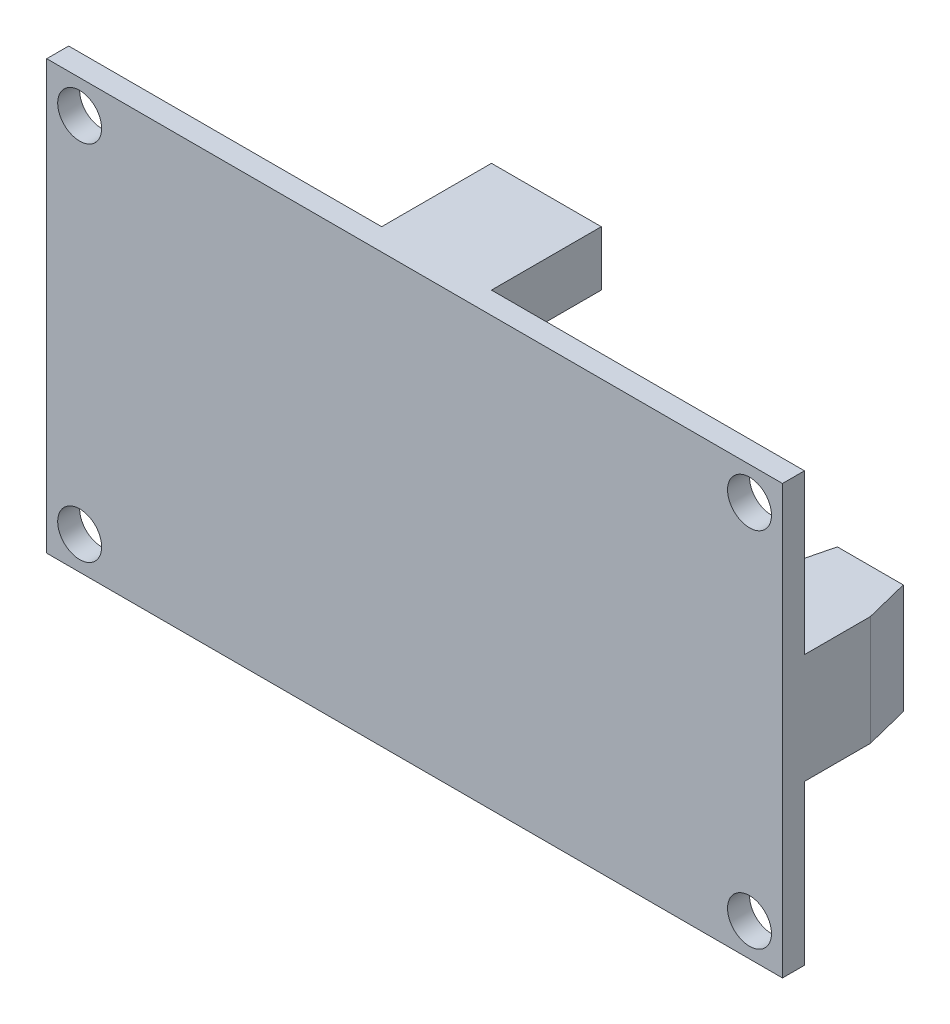
SolidWorks part; units mm, degrees
ref_plane "前视基准面" through (0, 0, 0) normal (0, 0, 1) x (1, 0, 0)
ref_plane "上视基准面" through (0, 0, 0) normal (0, 1, 0) x (1, 0, 0)
ref_plane "右视基准面" through (0, 0, 0) normal (1, 0, 0) x (0, 0, -1)
sketch "草图1" plane through (0, 0, 0) normal (0, 0, 1) x (1, 0, 0)
  line L1 (-33.5, 19.5) -> (33.5, 19.5)
  line L2 (-33.5, 19.5) -> (-33.5, -19.5)
  line L3 (-33.5, -19.5) -> (33.5, -19.5)
  line L4 (33.5, 19.5) -> (33.5, -19.5)
  line L5 (-33.5, 19.5) -> (33.5, -19.5) construction
  line L6 (-33.5, -19.5) -> (33.5, 19.5) construction
  point P0 (0, 0)
  dimension "D1" = 67
  dimension "D2" = 39
extrude "凸台-拉伸1" add sketch "草图1" along normal blind 2
sketch "草图2" plane through (0, 0, 2) normal (0, 0, 1) x (1, 0, 0)
  line L0 (33.5, 19.5) -> (-33.5, 19.5) construction
  line L1 (-33.5, 19.5) -> (-33.5, -19.5) construction
  circle A0 centre (-30.5, 16.5) radius 2
  dimension "D1" = 4
  dimension "D2" = 3
  dimension "D3" = 3
extrude "切除-拉伸1" cut sketch "草图2" against normal blind 2
mirror "镜向1" about plane through (0, 0, 0) normal (1, 0, 0) of "切除-拉伸1"
mirror "镜向2" about plane through (0, 0, 0) normal (0, 1, 0) of "镜向1", "切除-拉伸1"
sketch "草图3" plane through (0, 0, 0) normal (0, 0, -1) x (-1, 0, 0)
  line L0 (-33.5, -19.5) -> (-33.5, 19.5) construction
  line L1 (-33.5, 5) -> (-25.5, 5)
  line L2 (-33.5, 5) -> (-33.5, -5)
  line L3 (-33.5, -5) -> (-25.5, -5)
  line L4 (-25.5, 5) -> (-25.5, -5)
  dimension "D1" = 10
  dimension "D2" = 8
  dimension "D3" = 5
extrude "凸台-拉伸2" add sketch "草图3" along normal blind 10
sketch "草图4" plane through (0, -5, 0) normal (0, -1, 0) x (1, 0, 0)
  line L0 (29.5, -10) -> (29.5, -4.0659) construction
  line L1 (33.5, -10) -> (25.5, -10) construction
  line L2 (32.5, -10) -> (33.5, -6)
  line L3 (33.5, -10) -> (33.5, 0) construction
  line L4 (32.5, -10) -> (33.5, -10)
  line L5 (33.5, -10) -> (33.5, -6)
  line L6 (25.5, -10) -> (25.5, -6)
  line L7 (26.5, -10) -> (25.5, -10)
  line L8 (26.5, -10) -> (25.5, -6)
  dimension "D1" = 4
  dimension "D2" = 1
extrude "切除-拉伸2" cut sketch "草图4" against normal blind 10
sketch "草图5" plane through (0, 0, -10) normal (0, 0, -1) x (-1, 0, 0)
  line L0 (-26.5, 5) -> (-32.5, 5) construction
  line L1 (-33.5, -5) -> (-25.5, -5) construction
  circle A0 centre (-29.5, 2) radius 1.5
  circle A1 centre (-29.5, -2) radius 1.5
  point P6 (-29.5, 5)
  dimension "D1" = 3
  dimension "D2" = 3
  dimension "D3" = 3
  dimension "D4" = 3
extrude "切除-拉伸3" cut sketch "草图5" against normal blind 8
mirror "镜向3" about plane through (0, 0, 0) normal (1, 0, 0) of "凸台-拉伸2", "切除-拉伸2", "切除-拉伸3"
sketch "草图6" plane through (0, 0, 0) normal (0, 0, -1) x (-1, 0, 0)
  line L0 (-33.5, 19.5) -> (33.5, 19.5) construction
  line L1 (-5, 19.5) -> (5, 19.5)
  line L2 (-5, 19.5) -> (-5, 14.5)
  line L3 (-5, 14.5) -> (5, 14.5)
  line L4 (5, 19.5) -> (5, 14.5)
  dimension "D1" = 10
  dimension "D2" = 5
  dimension "D3" = 5
extrude "凸台-拉伸3" add sketch "草图6" along normal blind 10
sketch "草图10" plane through (0, 0, 0) normal (0, 0, -1) x (-1, 0, 0)
  line L0 (33.5, -19.5) -> (-33.5, -19.5) construction
  line L1 (11.5, -19.5) -> (-11.5, -19.5)
  line L2 (11.5, -19.5) -> (11.5, -5.5)
  line L3 (11.5, -5.5) -> (-11.5, -5.5)
  line L4 (-11.5, -19.5) -> (-11.5, -5.5)
  dimension "D1" = 23
  dimension "D2" = 14
  dimension "D3" = 11.5
extrude "凸台-拉伸4" add sketch "草图10" along normal blind 7.5
